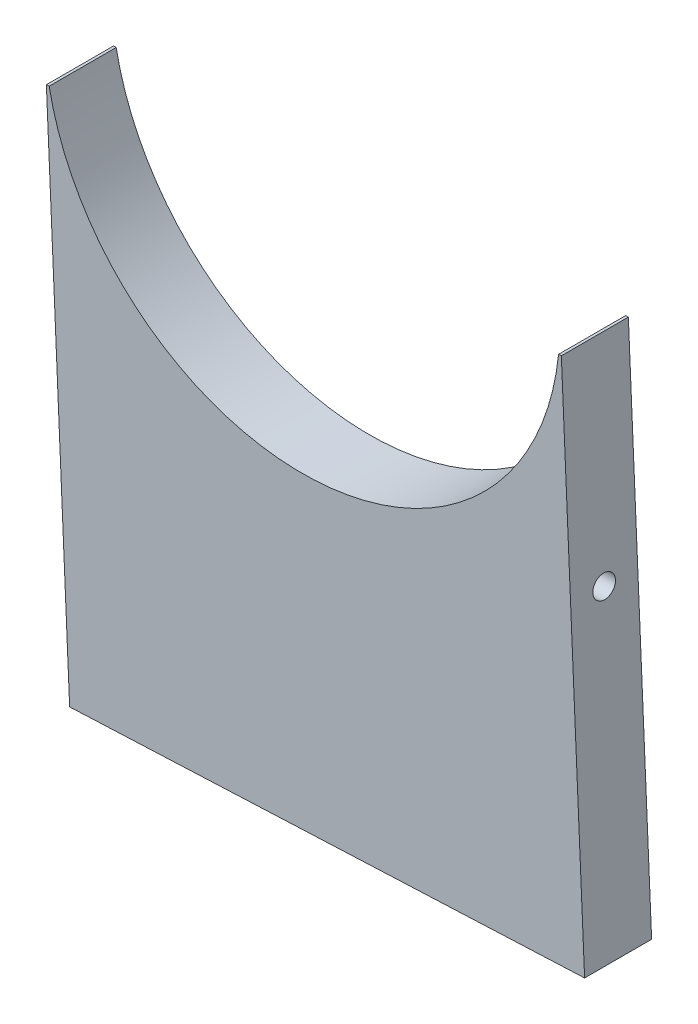
SolidWorks part; units mm, degrees
ref_plane "Front Plane" through (0, 0, 0) normal (0, 0, 1) x (1, 0, 0)
ref_plane "Top Plane" through (0, 0, 0) normal (0, 1, 0) x (1, 0, 0)
ref_plane "Right Plane" through (0, 0, 0) normal (1, 0, 0) x (0, 0, -1)
sketch "Sketch1" plane through (0, 0, 0) normal (0, 0, 1) x (-0.0441, 0.999, 0)
  line L0 (-5.9977, -62.8167) -> (-5.9977, -63.5519)
  line L2 (-5.9977, 73.1881) -> (-145.9977, 73.1881)
  line L3 (-5.9977, -63.5519) -> (-145.9977, -63.5519)
  line L4 (-145.9977, -63.5519) -> (-145.9977, 73.1881)
  line L5 (-5.9977, 73.1881) -> (-5.9977, 72.4528)
  arc A3 (-5.9977, 72.4528) -> (-5.9977, -62.8167) centre (4.0023, 4.8181) ccw
extrude "Boss-Extrude1" add sketch "Sketch1" along normal blind 17.78
sketch "Sketch2" plane through (0.2644, -5.9919, 0) normal (-0.0441, 0.999, 0) x (0.999, 0.0441, 0)
  line L0 (-73.1881, -13.14) -> (63.5519, -13.14)
  line L1 (63.5519, -13.14) -> (63.5519, -4.64)
  line L5 (-73.1881, -4.64) -> (63.5519, -4.64)
  line L6 (-73.1881, -4.64) -> (-73.1881, -13.14)
sketch "Sketch3" plane through (-73.1169, -3.2261, 0) normal (-0.999, -0.0441, 0) x (0, 0, 1)
  line L0 (8.89, -34.3044) -> (8.89, -90.151) construction
  line L3 (8.89, -90.151) -> (17.78, -90.151) construction
  line L4 (17.78, -5.9977) -> (17.78, -145.9977) construction
  circle A0 centre (8.89, -62.2277) radius 3
  dimension "D1" = 6
extrude "Cut-Extrude3" cut sketch "Sketch3" against normal blind 6
sketch "Sketch4" plane through (63.4902, 2.8014, 0) normal (0.999, 0.0441, 0) x (0, 0, -1)
  line L0 (-8.89, -34.3044) -> (-8.89, -90.151) construction
  line L3 (-8.89, -90.151) -> (0, -90.151) construction
  line L4 (0, -145.9977) -> (0, -5.9977) construction
  circle A0 centre (-8.89, -62.2277) radius 3
extrude "Cut-Extrude4" cut sketch "Sketch4" against normal blind 6
sketch "Sketch5" plane through (6.4356, -145.8558, 0) normal (0.0441, -0.999, 0) x (0.999, 0.0441, 0)
  line L3 (-4.8181, 17.78) -> (-4.8181, 0) construction
  line L4 (-73.1881, 17.78) -> (63.5519, 17.78) construction
  point P1 (-39.0031, 8.89)
  point P4 (29.3669, 8.89)
hole_wizard "Tap Drill for M4x0.7 Tap1" positions "3DSketch1" profile "Sketch6" hole size "M4x0.7" standard "Ansi Metric"
sketch3d "3DSketch1"
  point P0 (-32.5296, -147.5751, 8.89)
  point P3 (35.774, -144.5613, 8.89)
sketch "Sketch6" plane through (-32.5296, -147.5751, 8.89) normal (0, 0, 1) x (0.999, 0.0441, 0)
  line L0 (0, 0) -> (0, 10.9914)
  line L1 (0, 10.9914) -> (1.65, 10)
  line L2 (1.65, 10) -> (1.65, 0)
  line L5 (1.65, 0) -> (0, 0)
  line L10 (0, 10.9914) -> (-1.65, 10) construction
  line L11 (0, -6.35) -> (0, 107.95) construction
  dimension "Hole Dia." = 3.3
  dimension "Hole Depth" = 10
  dimension "Drill Angle" = 118
sketch "Sketch7" plane through (6.4356, -145.8558, 0) normal (0.0441, -0.999, 0) x (0.999, 0.0441, 0)
  line L0 (-73.1881, 8.89) -> (-39.0031, 8.89) construction
  line L1 (-73.1881, 17.78) -> (-73.1881, 0) construction
  line L2 (-39.0031, 8.89) -> (29.3669, 8.89) construction
  line L3 (29.3669, 8.89) -> (63.5519, 8.89) construction
  line L4 (63.5519, 17.78) -> (63.5519, 0) construction
